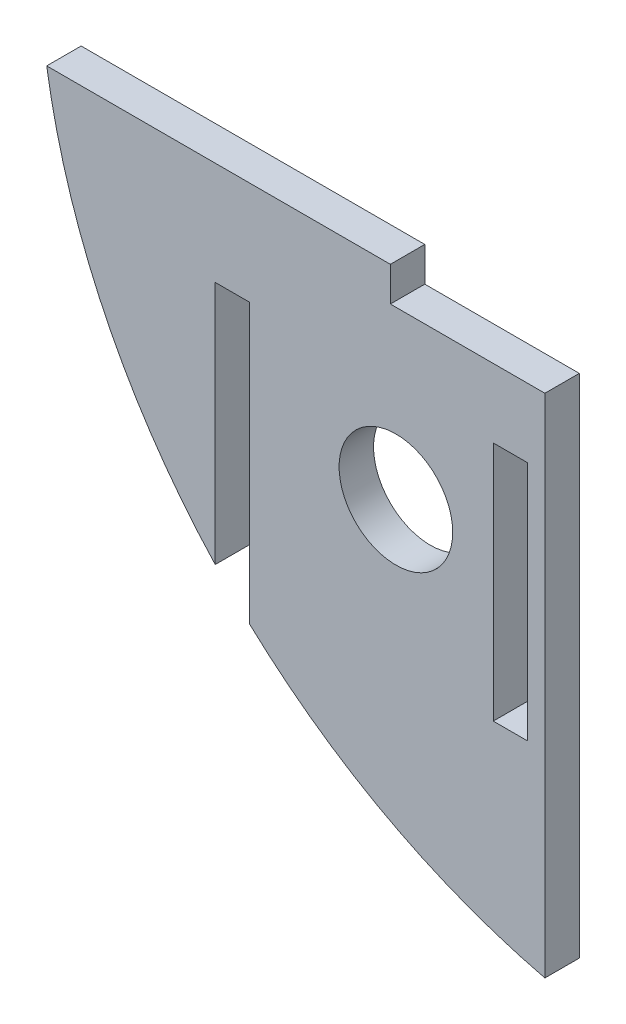
SolidWorks part; units mm, degrees
ref_plane "Front Plane" through (0, 0, 0) normal (0, 0, 1) x (1, 0, 0)
ref_plane "Top Plane" through (0, 0, 0) normal (0, 1, 0) x (1, 0, 0)
ref_plane "Right Plane" through (0, 0, 0) normal (1, 0, 0) x (0, 0, -1)
sketch "Sketch1" plane through (0, 0, 0) normal (0, 0, 1) x (1, 0, 0)
  line L0 (-19.2534, 9.7141) -> (-19.2534, -6.4891)
  line L2 (-5.097, -4.2859) -> (-5.097, 9.7141)
  line L3 (-19.2534, 9.7141) -> (-21.2534, 9.7141)
  line L4 (-11.0757, 13.7141) -> (-11.0757, 15.7141)
  line L5 (-11.0757, 13.7141) -> (-2.097, 13.7141)
  line L6 (-11.0757, 15.7141) -> (-31.0457, 15.7141)
  line L7 (-5.097, -4.2859) -> (-3.097, -4.2859)
  line L8 (-3.097, -4.2859) -> (-3.097, 9.7141)
  line L9 (-3.097, 9.7141) -> (-5.097, 9.7141)
  line L10 (-21.2534, 9.7141) -> (-21.2534, -4.4854)
  line L11 (-2.097, -15.7141) -> (-2.097, 13.7141)
  circle A0 centre (-10.7534, 4.0364) radius 3.3
  arc A1 (-31.0457, 15.7141) -> (-21.2534, -4.4854) centre (6.9377, 21.6543) ccw
  arc A2 (-19.2534, -6.4891) -> (-2.097, -15.7141) centre (6.9377, 21.6543) ccw
extrude "Boss-Extrude1" add sketch "Sketch1" along normal blind 2
